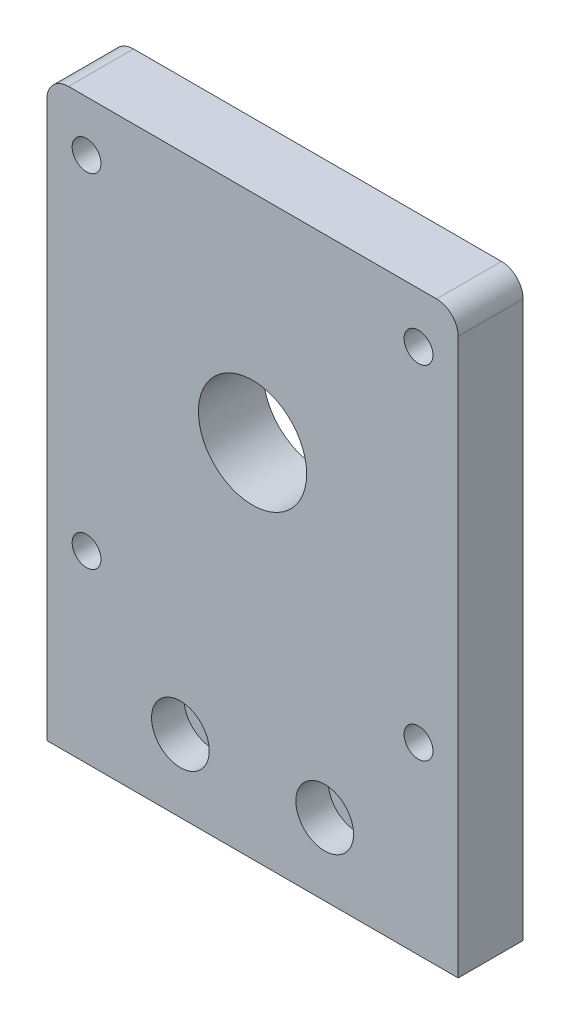
SolidWorks part; units mm, degrees
material "AISI 1035 Acero (SS)"
ref_plane "Alzado" through (0, 0, 0) normal (0, 0, 1) x (1, 0, 0)
ref_plane "Planta" through (0, 0, 0) normal (0, 1, 0) x (1, 0, 0)
ref_plane "Vista lateral" through (0, 0, 0) normal (1, 0, 0) x (0, 0, -1)
sketch "Croquis1" plane through (0, 0, 0) normal (0, 0, 1) x (1, 0, 0)
  line L0 (0, 0) -> (0, 61.5479) construction
  line L1 (-25.5, 40) -> (25.5, 40)
  line L2 (-28.5, 37) -> (-28.5, -40)
  line L3 (-28.5, -40) -> (28.5, -40)
  line L4 (28.5, 37) -> (28.5, -40)
  line L5 (-28.5, 40) -> (28.5, -40) construction
  line L6 (-28.5, -40) -> (28.5, 40) construction
  arc A0 (25.5, 40) -> (28.5, 37) centre (25.5, 37) cw
  arc A1 (-25.5, 40) -> (-28.5, 37) centre (-25.5, 37) ccw
  circle A2 centre (0, 10) radius 7.5
  circle A3 centre (10, -30) radius 2
  circle A4 centre (-10, -30) radius 2
  circle A5 centre (-23, 33) radius 2
  circle A6 centre (-23, -14.5) radius 2
  circle A7 centre (23, -14.5) radius 2
  circle A8 centre (23, 33) radius 2
  point P0 (0, 0)
  dimension "D3" = 3
  dimension "D4" = 50
  dimension "D5" = 15
  dimension "D6" = 10
  dimension "D7" = 20
  dimension "D9" = 5.5
  dimension "D11" = 4
  dimension "D12" = 47.5
  dimension "D1" = 80
  dimension "D2" = 57
  dimension "D8" = 10
  dimension "D10" = 7
extrude "Saliente-Extruir1" add sketch "Croquis1" along normal blind 9
sketch "Croquis2" plane through (0, 0, 9) normal (0, 0, 1) x (1, 0, 0)
  circle A0 centre (-10, -30) radius 4
  circle A1 centre (10, -30) radius 4
extrude "Cortar-Extruir1" cut sketch "Croquis2" against normal blind 4.5
